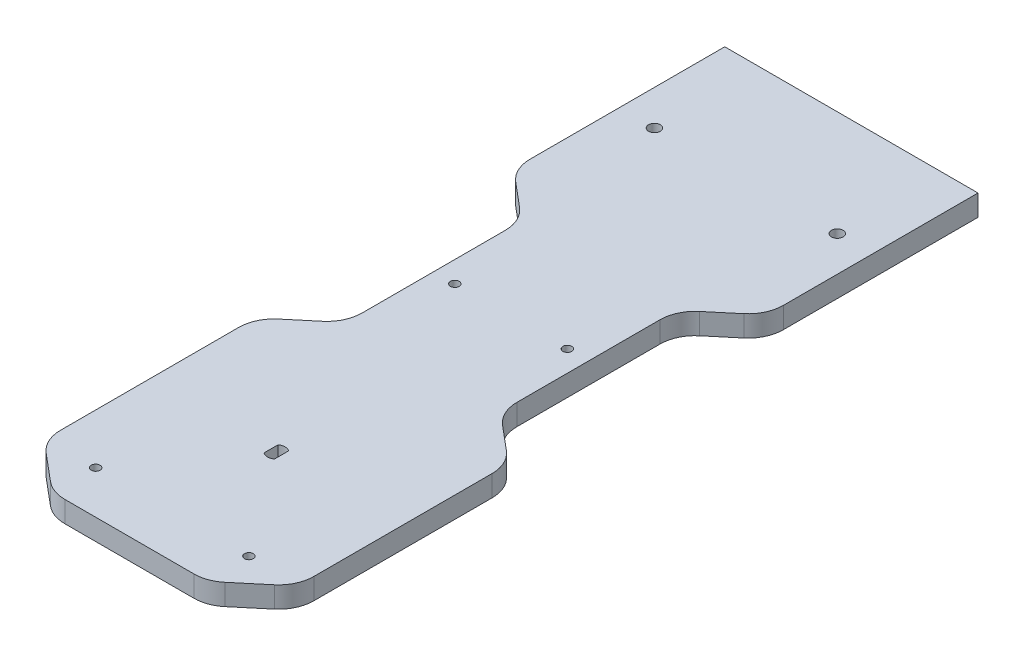
SolidWorks part; units mm, degrees
ref_plane "Front Plane" through (0, 0, 0) normal (0, 0, 1) x (1, 0, 0)
ref_plane "Top Plane" through (0, 0, 0) normal (0, 1, 0) x (1, 0, 0)
ref_plane "Right Plane" through (0, 0, 0) normal (1, 0, 0) x (0, 0, -1)
sketch "Sketch1" plane through (0, 0, 0) normal (0, 1, 0) x (1, 0, 0)
  line L0 (21.2131, -102.2276) -> (35.2131, -90.4802)
  line L1 (35.2131, -90.4802) -> (35.2131, -30.4802)
  line L2 (35.2131, -30.4802) -> (21.2131, -18.7328)
  line L3 (21.2131, -18.7328) -> (21.2131, 31.2672)
  line L4 (21.2131, 31.2672) -> (35.2131, 43.0146)
  line L5 (35.2131, 43.0146) -> (35.2131, 103.0146)
  line L6 (35.2131, 103.0146) -> (-36.7869, 103.0146)
  line L7 (-36.7869, 103.0146) -> (-36.7869, 43.0146)
  line L8 (-36.7869, 43.0146) -> (-22.7869, 31.2672)
  line L9 (-22.7869, 31.2672) -> (-22.7869, -18.7328)
  line L10 (-22.7869, -18.7328) -> (-36.7869, -30.4802)
  line L11 (-36.7869, -30.4802) -> (-36.7869, -90.4802)
  line L12 (-36.7869, -90.4802) -> (-22.7869, -102.2276)
  line L13 (-22.7869, -102.2276) -> (21.2131, -102.2276)
extrude "Boss-Extrude1" add sketch "Sketch1" along normal blind 6
fillet "Fillet1" radius 10 8 edges at (35.2131, 3, 30.4802) (21.2131, 3, 18.7328) (-22.7869, 3, 18.7328) (-36.7869, 3, 30.4802) (35.2131, 3, 90.4802) (21.2131, 3, 102.2276) (-22.7869, 3, 102.2276) (-36.7869, 3, 90.4802)
sketch "Sketch2" plane through (0, 0, 0) normal (0, -1, 0) x (1, 0, 0)
  line L1 (-36.7869, 60.4802) -> (21.737, 60.4802) construction
  line L2 (-36.7869, 35.1433) -> (-36.7869, 85.8172) construction
  circle A0 centre (-0.7869, 60.4802) radius 2.5
  dimension "D2" = 5
  dimension "D1" = 36
extrude "Cut-Extrude1" cut sketch "Sketch2" against normal blind 6
sketch "Sketch4" plane through (0, 0, 0) normal (0, -1, 0) x (1, 0, 0)
  line L0 (35.2131, -43.0146) -> (35.2131, -103.0146) construction
  line L1 (-36.7869, -103.0146) -> (35.2131, -103.0146)
  line L2 (-36.7869, -103.0146) -> (-36.7869, -99.0146)
  line L3 (-36.7869, -99.0146) -> (35.2131, -99.0146)
  line L4 (35.2131, -103.0146) -> (35.2131, -99.0146)
  dimension "D1" = 4
fillet "Fillet2" radius 10 4 edges at (21.2131, 3, -31.2672) (35.2131, 3, -43.0146) (-22.7869, 3, -31.2672) (-36.7869, 3, -43.0146)
sketch "Sketch5" plane through (0, 6, 0) normal (0, 1, 0) x (1, 0, 0)
  circle A0 centre (15.2131, 6.2672) radius 1.25
  circle A1 centre (-16.7869, 6.2672) radius 1.25
  dimension "D1" = 2.5
  dimension "D2" = 2.5
extrude "Cut-Extrude2" cut sketch "Sketch5" against normal blind 10
sketch "Sketch6" plane through (0, 0, 0) normal (0, -1, 0) x (1, 0, 0)
  circle A0 centre (-22.5674, 90.0433) radius 1.25
  circle A1 centre (20.9936, 90.0433) radius 1.25
extrude "Cut-Extrude3" cut sketch "Sketch6" against normal blind 10
sketch "Sketch7" plane through (0, 6, 0) normal (0, 1, 0) x (1, 0, 0)
  circle A0 centre (25.2131, 73.0146) radius 1.65
  circle A1 centre (-26.7869, 73.0146) radius 1.65
  dimension "D1" = 3.3
extrude "Cut-Extrude4" cut sketch "Sketch7" against normal blind 10
sketch "Sketch8" plane through (0, 6, 0) normal (0, 1, 0) x (1, 0, 0)
  line L0 (-2.2869, -57.8822) -> (-2.2869, -63.0783)
  line L1 (0.7131, -57.8822) -> (0.7131, -63.0783)
  arc A0 (-2.2869, -57.8822) -> (-2.2869, -63.0783) centre (-0.7869, -60.4802) ccw
  arc A1 (0.7131, -63.0783) -> (0.7131, -57.8822) centre (-0.7869, -60.4802) ccw
  dimension "D3" = 6
  dimension "D1" = 1.5
  dimension "D2" = 1.5
extrude "Boss-Extrude2" add sketch "Sketch8" against normal blind 6
